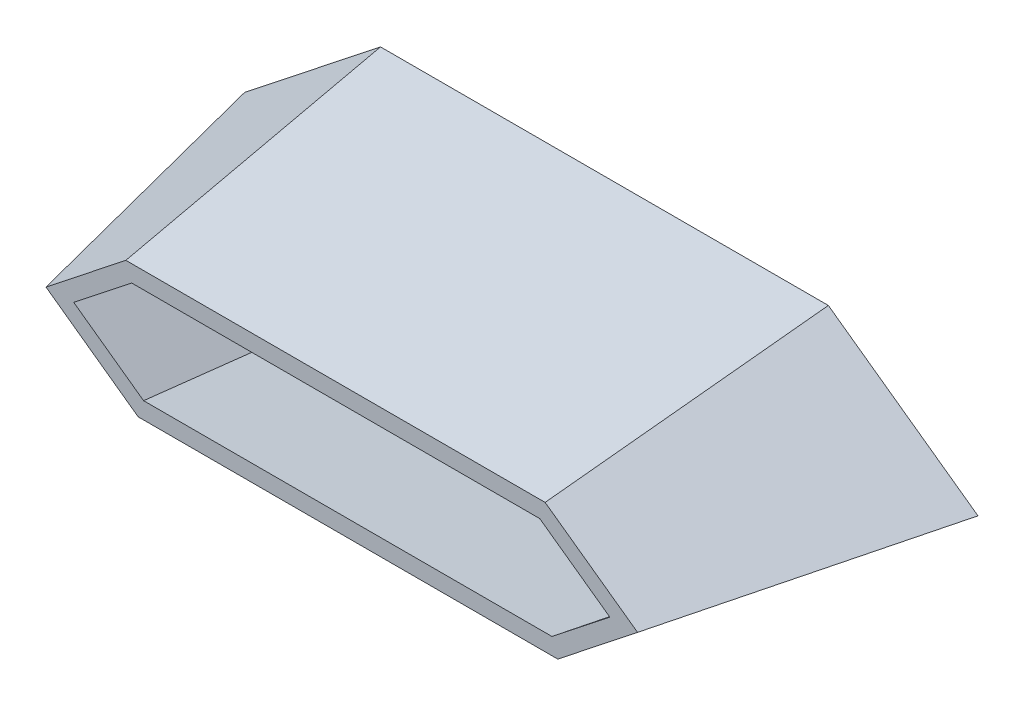
SolidWorks part; units mm, degrees
ref_plane "Ebene vorne" through (0, 0, 0) normal (0, 0, 1) x (1, 0, 0)
ref_plane "Ebene oben" through (0, 0, 0) normal (0, 1, 0) x (1, 0, 0)
ref_plane "Ebene rechts" through (0, 0, 0) normal (1, 0, 0) x (0, 0, -1)
sketch "Skizze1" plane through (0, 0, 0) normal (0, 0, 1) x (1, 0, 0)
  line L0 (19.8659, 0) -> (11.7582, 5.8172)
  line L1 (11.7582, 5.8172) -> (-12.5035, 5.8172)
  line L2 (-12.5035, 5.8172) -> (-19.8659, 0)
  line L3 (-19.8659, 0) -> (-11.7764, -5.8172)
  line L4 (-11.7764, -5.8172) -> (-11.1764, -5.8172)
  line L5 (-11.1764, -5.8172) -> (-3.4764, -5.8172)
  line L6 (-3.4764, -5.8172) -> (4.2236, -5.8172)
  line L7 (4.2236, -5.8172) -> (11.9236, -5.8172)
  line L8 (11.9236, -5.8172) -> (12.5035, -5.8172)
  line L9 (12.5035, -5.8172) -> (19.8659, 0)
extrude "Linear-Austragen-Dünn1" add sketch "Skizze1" along normal blind 0.6 thin thin type one direction reverse wall 1
sketch "Skizze2" plane through (0, 0, 0.6) normal (0, 0, 1) x (1, 0, 0)
  line L0 (-12.1561, 4.8172) -> (-18.2054, 0.0376) construction
  line L1 (-18.2054, 0.0376) -> (-11.4542, -4.8172) construction
  line L2 (-11.4542, -4.8172) -> (12.1561, -4.8172) construction
  line L3 (12.1561, -4.8172) -> (18.2042, -0.0385) construction
  line L4 (18.2042, -0.0385) -> (11.4366, 4.8172) construction
  line L5 (11.4366, 4.8172) -> (-12.1561, 4.8172) construction
  line L6 (-12.1561, 4.8172) -> (-18.2054, 0.0376)
  line L7 (-18.2054, 0.0376) -> (-11.4542, -4.8172)
  line L8 (-11.4542, -4.8172) -> (12.1561, -4.8172)
  line L9 (12.1561, -4.8172) -> (18.2042, -0.0385)
  line L10 (18.2042, -0.0385) -> (11.4366, 4.8172)
  line L11 (11.4366, 4.8172) -> (-12.1561, 4.8172)
extrude "Linear-Austragen-Dünn2" add sketch "Skizze2" along normal blind 14 draft 9 thin
sketch "Skizze3" plane through (0, 0, 0) normal (0, 0, -1) x (-1, 0, 0)
  line L6 (-19.8659, 0) -> (-12.5035, -5.8172)
  line L7 (-12.5035, -5.8172) -> (11.7764, -5.8172)
  line L8 (11.7764, -5.8172) -> (19.8659, 0)
  line L9 (19.8659, 0) -> (12.5035, 5.8172)
  line L10 (12.5035, 5.8172) -> (-11.7582, 5.8172)
  line L11 (-11.7582, 5.8172) -> (-19.8659, 0)
  line L12 (-19.8659, 0) -> (-12.5035, -5.8172)
  line L13 (-12.5035, -5.8172) -> (11.7764, -5.8172)
  line L14 (11.7764, -5.8172) -> (19.8659, 0)
  line L15 (19.8659, 0) -> (12.5035, 5.8172)
  line L16 (12.5035, 5.8172) -> (-11.7582, 5.8172)
  line L17 (-11.7582, 5.8172) -> (-19.8659, 0)
  dimension "D1" = 0
extrude "Schnitt-Linear-Austragen-Dünn1" cut sketch "Skizze3" against normal blind 16 draft 9 thin
